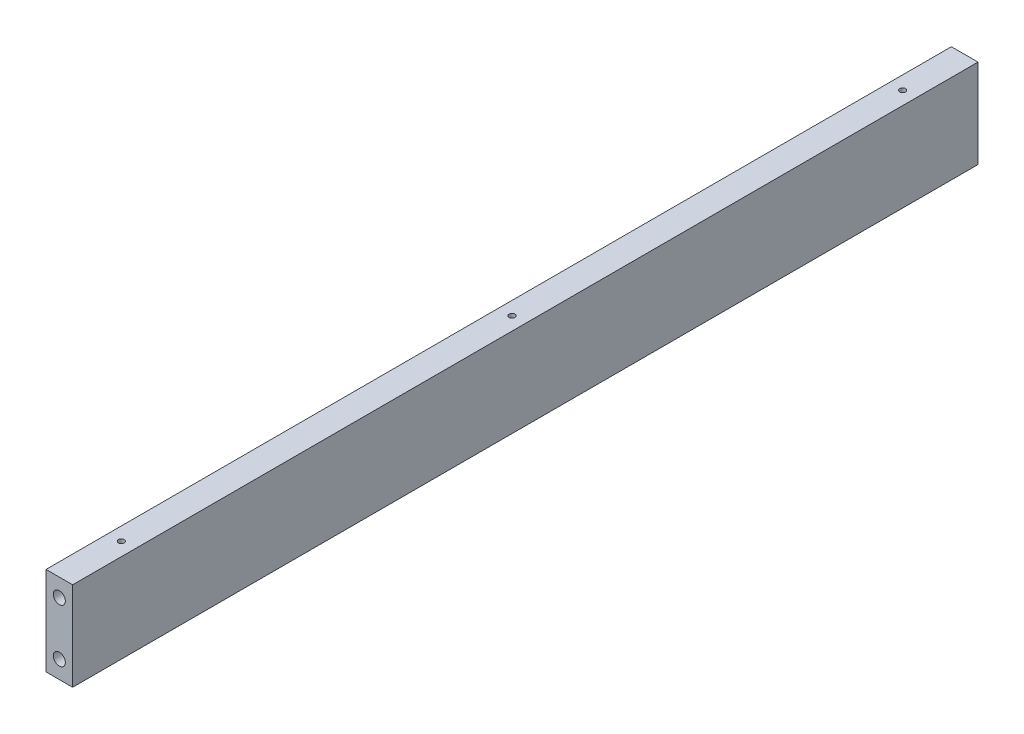
SolidWorks part; units mm, degrees
material "3.3549 (EN-AW 5182)"
ref_plane "Piano frontale" through (0, 0, 0) normal (0, 0, 1) x (1, 0, 0)
ref_plane "Piano superiore" through (0, 0, 0) normal (0, 1, 0) x (1, 0, 0)
ref_plane "Piano destro" through (0, 0, 0) normal (1, 0, 0) x (0, 0, -1)
sketch "Schizzo1" plane through (0, 0, 0) normal (0, 0, 1) x (1, 0, 0)
  line L0 (7.5, 25) -> (-7.5, -25) construction
  line L1 (-7.5, -25) -> (7.5, -25)
  line L2 (-7.5, -25) -> (-7.5, 25)
  line L3 (-7.5, 25) -> (7.5, 25)
  line L4 (7.5, -25) -> (7.5, 25)
  dimension "D1" = 15
  dimension "D2" = 50
extrude "Estrusione1" add sketch "Schizzo1" along normal mid plane 510
hole_wizard "Foro filettato M8-1" positions "Schizzo2" profile "Schizzo3" tap size "M8" standard "ISO"
sketch "Schizzo2" plane through (0, 0, 255) normal (0, 0, 1) x (1, 0, 0)
  line L0 (0, 15) -> (0, -15) construction
  point P0 (0, 15)
  point P2 (0, -15)
  dimension "D1" = 30
cosmetic thread "Filettatura del foro1" parameters "D1"=20, "D2"=8
cosmetic thread "Filettatura del foro2" parameters "D1"=20, "D2"=8
sketch "Schizzo3" plane through (0, 15, 255) normal (1, 0, 0) x (0, -1, 0)
  line L0 (0, 0) -> (0, 28.2929)
  line L1 (0, 28.2929) -> (3.4, 26.25)
  line L2 (3.4, 26.25) -> (3.4, 0)
  line L5 (3.4, 0) -> (0, 0)
  line L10 (0, 28.2929) -> (-3.4, 26.25) construction
  line L11 (0, -6.35) -> (0, 107.95) construction
  dimension "Tap Drill Dia." = 6.8
  dimension "Tap Drill Depth" = 26.25
  dimension "Drill Angle" = 118
mirror "Specchia1" about plane through (0, 0, 0) normal (0, 0, 1) of "Foro filettato M8-1"
hole_wizard "Foro filettato M4-1" positions "Schizzo4" profile "Schizzo5" tap size "M4" standard "ISO"
sketch "Schizzo4" plane through (0, 25, 0) normal (0, 1, 0) x (1, 0, 0)
  line L0 (0, 220) -> (0, -220) construction
  point P0 (0, 0)
  point P3 (0, 220)
  point P5 (0, -220)
  dimension "D1" = 440
sketch "Schizzo5" plane through (0, 25, 0) normal (1, 0, 0) x (0, 0, 1)
  line L0 (0, 0) -> (0, 16.4914)
  line L1 (0, 16.4914) -> (1.65, 15.5)
  line L2 (1.65, 15.5) -> (1.65, 0)
  line L5 (1.65, 0) -> (0, 0)
  line L10 (0, 16.4914) -> (-1.65, 15.5) construction
  line L11 (0, -6.35) -> (0, 107.95) construction
  dimension "Tap Drill Dia." = 3.3
  dimension "Tap Drill Depth" = 15.5
  dimension "Drill Angle" = 118
cosmetic thread "Filettatura del foro3" parameters "D1"=12, "D2"=4
cosmetic thread "Filettatura del foro4" parameters "D1"=12, "D2"=4
cosmetic thread "Filettatura del foro5" parameters "D1"=12, "D2"=4
